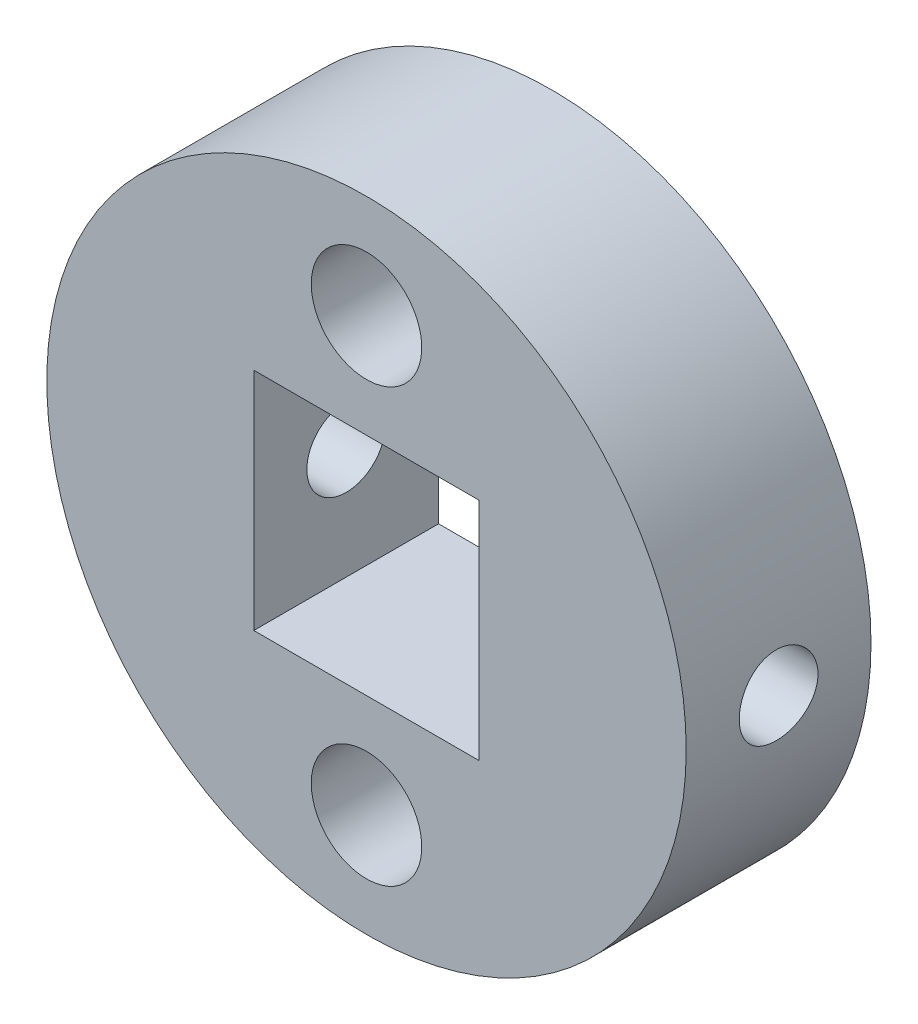
SolidWorks part; units mm, degrees
ref_plane "Front Plane" through (0, 0, 0) normal (0, 0, 1) x (1, 0, 0)
ref_plane "Top Plane" through (0, 0, 0) normal (0, 1, 0) x (1, 0, 0)
ref_plane "Right Plane" through (0, 0, 0) normal (1, 0, 0) x (0, 0, -1)
sketch "Sketch1" plane through (0, 0, 0) normal (0, 0, 1) x (1, 0, 0)
  line L1 (-3.8735, -3.8735) -> (3.8735, -3.8735)
  line L2 (-3.8735, -3.8735) -> (-3.8735, 3.8735)
  line L3 (-3.8735, 3.8735) -> (3.8735, 3.8735)
  line L4 (3.8735, -3.8735) -> (3.8735, 3.8735)
  line L5 (-3.8735, -3.8735) -> (3.8735, 3.8735) construction
  line L6 (-3.8735, 3.8735) -> (3.8735, -3.8735) construction
  circle A1 centre (0, 0) radius 10.9855
  dimension "D1" = 7.747
  dimension "D3" = 21.971
  dimension "D2" = 7.747
extrude "Boss-Extrude1" add sketch "Sketch1" along normal blind 6.35
ref_plane "Plane1" through (10.9855, 0, 0) normal (1, 0, 0) x (0, 0, -1)
sketch "Sketch3" plane through (3.8735, 0, 0) normal (-1, 0, 0) x (0, 0, 1)
  line L0 (3.175, 3.8735) -> (3.175, -3.8735) construction
  line L1 (6.35, 3.8735) -> (0, 3.8735) construction
  line L2 (6.35, -3.8735) -> (0, -3.8735) construction
  point P0 (3.175, 0)
sketch "Sketch4" plane through (10.9855, 0, 0) normal (1, 0, 0) x (0, 0, -1)
  point P0 (-3.175, 0)
ref_plane "Plane2" through (-10.9855, 0, 0) normal (-1, 0, 0) x (0, 0, 1)
sketch "Sketch5" plane through (-10.9855, 0, 0) normal (-1, 0, 0) x (0, 0, 1)
  point P0 (3.175, 0)
hole_wizard "#6-32 Tapped Hole1" positions "3DSketch2" profile "Sketch7" tap size "#6-32" standard "ANSI Inch"
sketch3d "3DSketch2"
  point P0 (10.9855, 0, 3.175)
  point P3 (10.9855, 0, 3.175)
  point P5 (10.9855, 0, 3.175)
  point P7 (10.9855, 0, 3.175)
  point P9 (10.9855, 0, 3.175)
  point P11 (10.9855, 0, 3.175)
  point P13 (10.9855, 0, 3.175)
  point P15 (3.8735, 0, 3.175)
sketch "Sketch7" plane through (3.8735, 0, 3.175) normal (0, 1, 0) x (0, 0, 1)
  line L0 (0, 0) -> (0, 7.112)
  line L1 (0, 7.112) -> (1.3525, 7.112)
  line L2 (1.3525, 7.112) -> (1.3525, 0)
  line L5 (1.3525, 0) -> (0, 0)
  line L11 (0, -6.35) -> (0, 107.95) construction
  dimension "Thru Tap Drill Dia." = 2.7051
  dimension "Thru Tap Drill Depth" = 7.112
cosmetic thread "Hole Thread1"
cosmetic thread "Hole Thread2"
cosmetic thread "Hole Thread3"
cosmetic thread "Hole Thread4"
cosmetic thread "Hole Thread5"
cosmetic thread "Hole Thread6"
cosmetic thread "Hole Thread7"
cosmetic thread "Hole Thread8"
sketch "Sketch9" plane through (-3.8735, 0, 0) normal (1, 0, 0) x (0, 0, -1)
  point P0 (-3.175, 0)
hole_wizard "#6-32 Tapped Hole2" positions "Sketch10" profile "Sketch11" tap size "#6-32" standard "ANSI Inch" end condition through all
sketch "Sketch10" plane through (-3.8735, 0, 0) normal (1, 0, 0) x (0, 0, -1)
  point P0 (-3.175, 0)
sketch "Sketch11" plane through (-3.8735, 0, 3.175) normal (0, 1, 0) x (0, 0, -1)
  line L0 (0, 0) -> (0, 7.112)
  line L1 (0, 7.112) -> (1.3525, 7.112)
  line L2 (1.3525, 7.112) -> (1.3525, 0)
  line L5 (1.3525, 0) -> (0, 0)
  line L11 (0, -6.35) -> (0, 107.95) construction
  dimension "Thru Tap Drill Dia." = 2.7051
  dimension "Thru Tap Drill Depth" = 7.112
cosmetic thread "Hole Thread9"
sketch "Sketch12" plane through (0, 0, 0) normal (0, 0, -1) x (-1, 0, 0)
  line L2 (3.8735, -3.8735) -> (-3.8735, -3.8735) construction
  line L3 (0, -3.8735) -> (0, -10.9855) construction
  line L4 (-10.9855, 0) -> (10.9855, 0) construction
  circle A0 centre (0, 0) radius 10.9855 construction
  point P2 (0, -7.4295)
  point P4 (0, -3.8735)
  point P6 (0, 7.4295)
hole_wizard "#6 Clearance Hole1" positions "Sketch15" profile "Sketch16" hole size "#6" standard "ANSI Inch" end condition through all
sketch "Sketch15" plane through (0, 0, 0) normal (0, 0, -1) x (-1, 0, 0)
  point P0 (0, -7.4295)
  point P3 (0, 7.4295)
sketch "Sketch16" plane through (0, -7.4295, 0) normal (1, 0, 0) x (0, 1, 0)
  line L0 (0, 0) -> (0, 6.35)
  line L1 (0, 6.35) -> (1.8986, 6.35)
  line L2 (1.8986, 6.35) -> (1.8986, 0)
  line L5 (1.8986, 0) -> (0, 0)
  line L11 (0, -6.35) -> (0, 107.95) construction
  dimension "Thru Hole Dia." = 3.7973
  dimension "Thru Hole Depth" = 6.35
sketch "Sketch17" plane through (0, 0, 6.35) normal (0, 0, 1) x (1, 0, 0)
  circle A0 centre (0, 0) radius 10.9855 construction
  point P0 (0, 10.9855)
